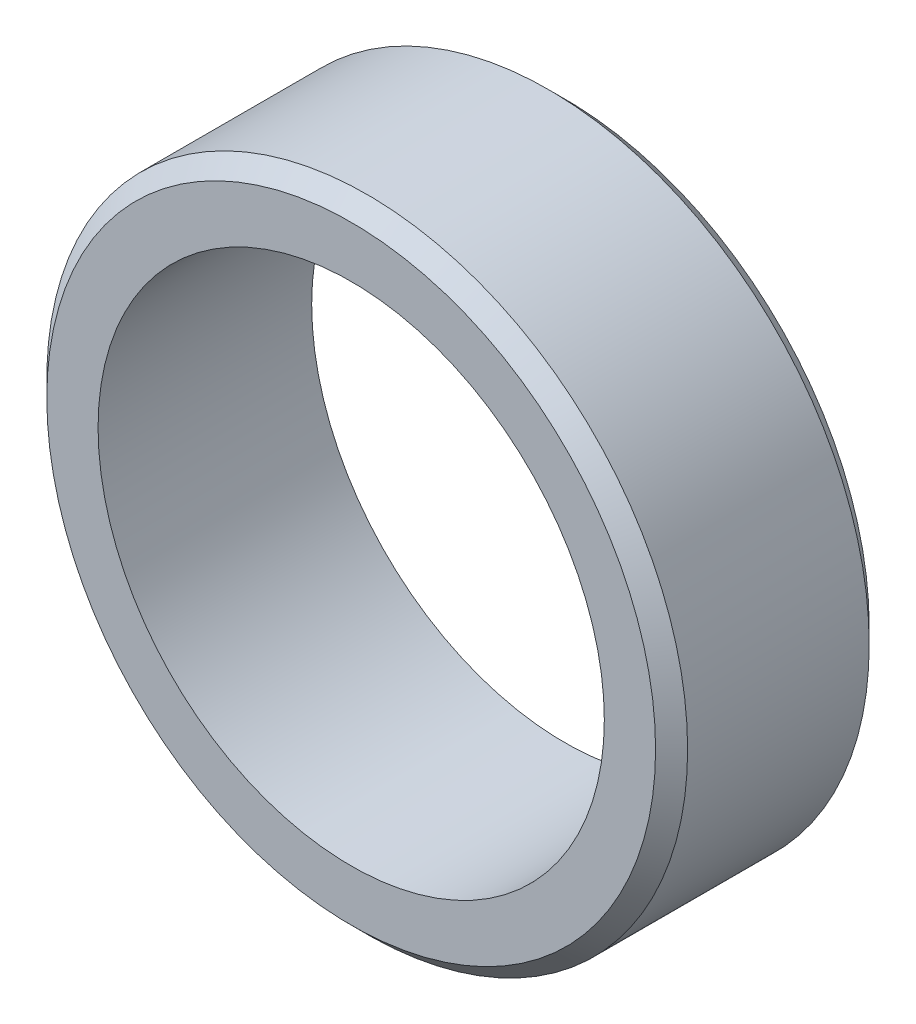
SolidWorks part; units mm, degrees
material "6061-O (SS)"
ref_plane "Front Plane" through (0, 0, 0) normal (0, 0, 1) x (1, 0, 0)
ref_plane "Top Plane" through (0, 0, 0) normal (0, 1, 0) x (1, 0, 0)
ref_plane "Right Plane" through (0, 0, 0) normal (1, 0, 0) x (0, 0, -1)
sketch "Sketch1" plane through (0, 0, 0) normal (0, 0, 1) x (1, 0, 0)
  circle A0 centre (0, 0) radius 19.05 construction
  circle A1 centre (0, 0) radius 9.525 construction
  point P4 (0, 19.05)
  dimension "ID" = 19.05
  dimension "OD" = 38.1
sketch "Sketch2" plane through (0, 0, 0) normal (1, 0, 0) x (0, 0, -1)
  line L0 (-7.9375, 19.05) -> (7.9375, 19.05) construction
  dimension "Length" = 15.875
sketch "Sketch3" plane through (0, 0, 0) normal (0, 0, 1) x (1, 0, 0)
  circle A0 centre (0, 0) radius 9.525 construction
  circle A1 centre (0, 0) radius 19.05 construction
  circle A2 centre (0, 0) radius 9.525
  circle A3 centre (0, 0) radius 19.05
extrude "Boss-Extrude1" add sketch "Sketch3" against normal up to vertex (7.9375 mm away) and the other way up to vertex (7.9375 mm away) up to point (0, 19.05, -7.9375) other way up to point (0, 19.05, 7.9375)
chamfer "Chamfer1" distance 0.9525 angle 45 4 edges at (19.05, 0, 7.9375) (19.05, 0, -7.9375) (9.525, 0, 7.9375) (9.525, 0, -7.9375)
sketch "Sketch4" plane through (0, 0, 7.9375) normal (0, 0, 1) x (1, 0, 0)
  circle A0 centre (0, 0) radius 19.05
extrude "Cut-Extrude1" cut sketch "Sketch4" against normal offset from surface (3.175 mm away) 12.7 up to face at (18.0975, 0, -7.9375)
sketch "Sketch5" plane through (0, 0, 4.7625) normal (0, 0, 1) x (1, 0, 0)
  circle A0 centre (0, 0) radius 15.0495
  dimension "D1" = 30.099
extrude "Cut-Extrude2" cut sketch "Sketch5" against normal through all
chamfer "Chamfer2" distance 0.9525 angle 45 1 edges at (19.05, 0, 4.7625)
equation "\"D1@Chamfer1\"=(\"OD@Sketch1\"-\"ID@Sketch1\")*0.05"
